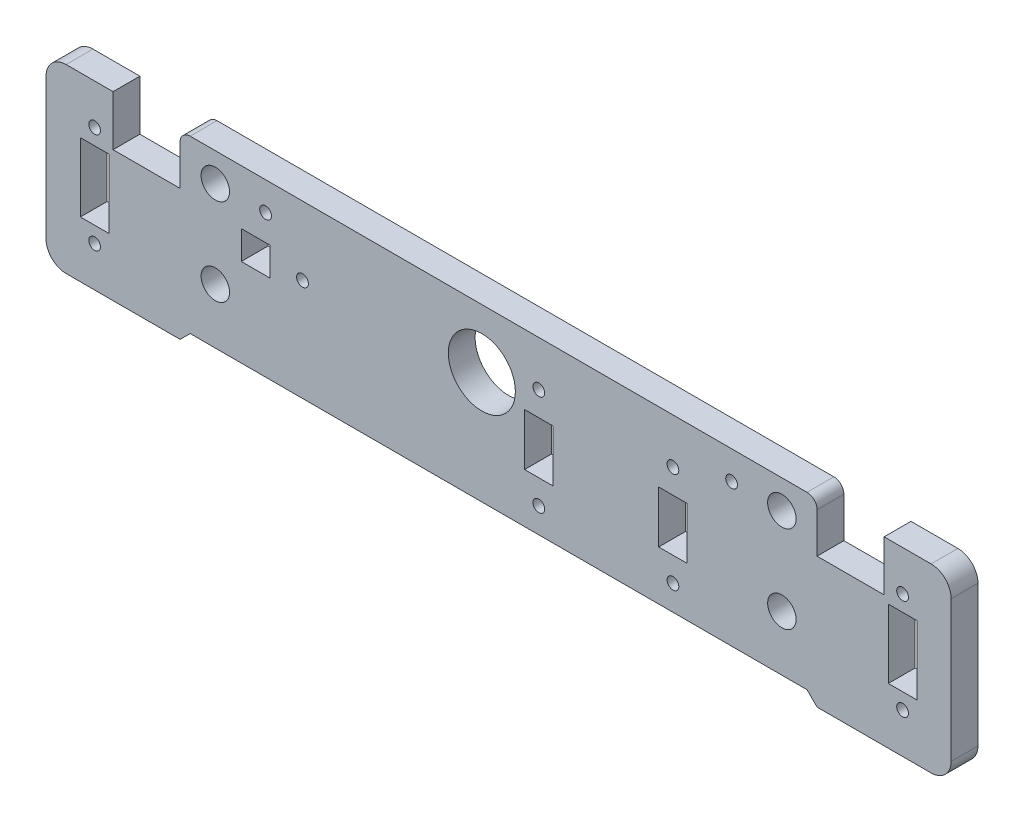
SolidWorks part; units mm, degrees
ref_plane "Front Plane" through (0, 0, 0) normal (0, 0, 1) x (1, 0, 0)
ref_plane "Top Plane" through (0, 0, 0) normal (0, 1, 0) x (1, 0, 0)
ref_plane "Right Plane" through (0, 0, 0) normal (1, 0, 0) x (0, 0, -1)
sketch "Sketch1" plane through (0, 0, 0) normal (0, 0, 1) x (1, 0, 0)
  line L0 (256.1348, 42.265) -> (264.6348, 42.265)
  line L1 (264.6348, 42.265) -> (264.6348, 21.765)
  line L2 (264.6348, 21.765) -> (256.1348, 21.765)
  line L3 (256.1348, 21.765) -> (256.1348, 42.265)
  line L4 (23.6348, 42.265) -> (15.1348, 42.265)
  line L5 (15.1348, 42.265) -> (15.1348, 21.765)
  line L6 (15.1348, 21.765) -> (23.6348, 21.765)
  line L7 (23.6348, 21.765) -> (23.6348, 42.265)
  line L8 (187.6348, 38.265) -> (196.1348, 38.265)
  line L9 (196.1348, 38.265) -> (196.1348, 22.765)
  line L10 (196.1348, 22.765) -> (187.6348, 22.765)
  line L11 (187.6348, 22.765) -> (187.6348, 38.265)
  line L12 (147.6348, 38.265) -> (156.1348, 38.265)
  line L13 (156.1348, 38.265) -> (156.1348, 22.765)
  line L14 (156.1348, 22.765) -> (147.6348, 22.765)
  line L15 (147.6348, 22.765) -> (147.6348, 38.265)
  line L16 (63.1348, 42.765) -> (71.6348, 42.765)
  line L17 (71.6348, 42.765) -> (71.6348, 34.265)
  line L18 (71.6348, 34.265) -> (63.1348, 34.265)
  line L19 (63.1348, 34.265) -> (63.1348, 42.765)
  line L20 (234.8848, 56.015) -> (234.8848, 44.015)
  line L21 (234.8848, 44.015) -> (254.8848, 44.015)
  line L22 (254.8848, 44.015) -> (254.8848, 59.015)
  line L23 (254.8848, 59.015) -> (268.8848, 59.015)
  line L24 (274.8848, 53.015) -> (274.8848, 11.015)
  line L25 (268.8848, 5.015) -> (234.8848, 5.015)
  line L26 (234.8848, 5.015) -> (231.8848, 8.015)
  line L27 (231.8848, 8.015) -> (47.8848, 8.015)
  line L28 (47.8848, 8.015) -> (44.8848, 5.015)
  line L29 (44.8848, 5.015) -> (10.8848, 5.015)
  line L30 (4.8848, 11.015) -> (4.8848, 53.015)
  line L31 (10.8848, 59.015) -> (24.8848, 59.015)
  line L32 (24.8848, 59.015) -> (24.8848, 44.015)
  line L33 (24.8848, 44.015) -> (44.8848, 44.015)
  line L34 (44.8848, 44.015) -> (44.8848, 56.015)
  line L35 (47.8848, 59.015) -> (231.8848, 59.015)
  line L36 (139.8848, 59.015) -> (139.8848, 8.015) construction
  line L37 (55.3848, 50.515) -> (70.3848, 50.515) construction
  circle A0 centre (260.3848, 47.015) radius 1.75
  circle A1 centre (260.3848, 17.015) radius 1.75
  circle A2 centre (19.3848, 47.015) radius 1.75
  circle A3 centre (19.3848, 17.015) radius 1.75
  circle A4 centre (224.3848, 50.515) radius 4.25
  circle A5 centre (224.3848, 24.515) radius 4.25
  circle A6 centre (55.3848, 50.515) radius 4.25
  circle A7 centre (55.3848, 24.515) radius 4.25
  circle A8 centre (191.8848, 15.515) radius 1.75
  circle A9 centre (191.8848, 45.515) radius 1.75
  circle A10 centre (151.8848, 15.515) radius 1.75
  circle A11 centre (151.8848, 45.515) radius 1.75
  circle A12 centre (81.3848, 38.515) radius 1.75
  circle A13 centre (70.3848, 50.515) radius 1.75
  circle A14 centre (134.8848, 41.515) radius 10
  arc A15 (274.8848, 53.015) -> (268.8848, 59.015) centre (268.8848, 53.015) ccw
  arc A16 (268.8848, 5.015) -> (274.8848, 11.015) centre (268.8848, 11.015) ccw
  arc A17 (4.8848, 11.015) -> (10.8848, 5.015) centre (10.8848, 11.015) ccw
  arc A18 (10.8848, 59.015) -> (4.8848, 53.015) centre (10.8848, 53.015) ccw
  arc A19 (47.8848, 59.015) -> (44.8848, 56.015) centre (47.8848, 56.015) ccw
  arc A20 (234.8848, 56.015) -> (231.8848, 59.015) centre (231.8848, 56.015) ccw
  circle A21 centre (209.3848, 50.515) radius 1.75
  dimension "D2" = 15
  dimension "D3" = 17.5
  dimension "D7" = 20
  dimension "D4" = 5
  dimension "D1" = 25.5
  dimension "D5" = 5.015
  dimension "D6" = 4.8848
  dimension "D8" = 270
  dimension "D9" = 54
extrude "Extrude1" add sketch "Sketch1" along normal blind 8
